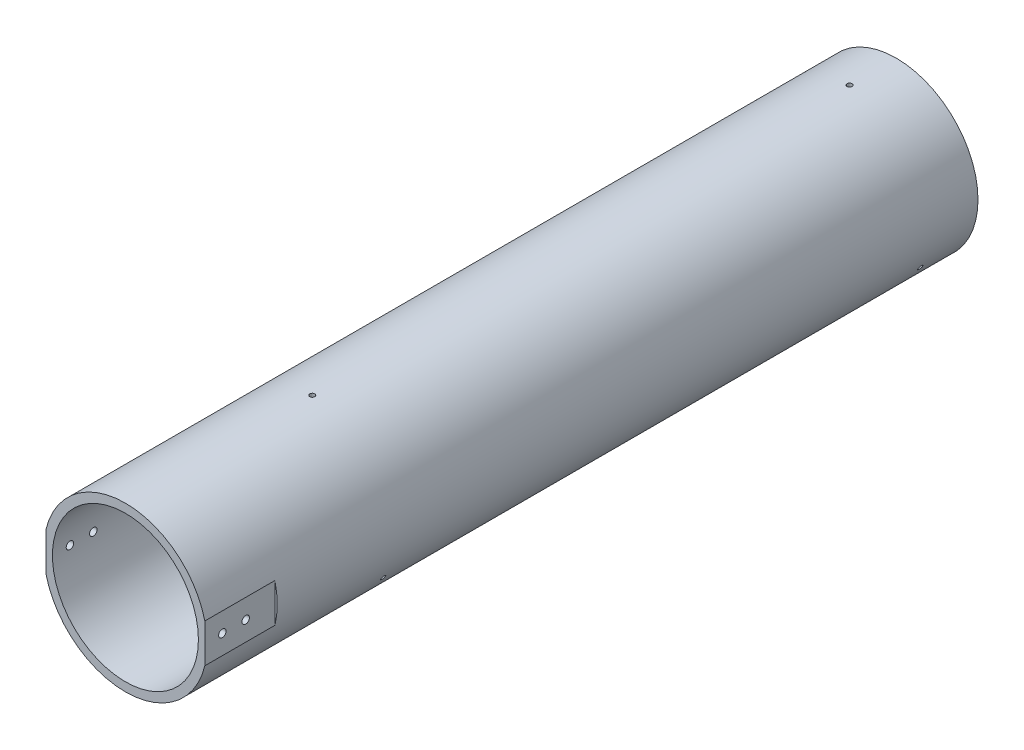
SolidWorks part; units mm, degrees
ref_plane "Front Plane" through (0, 0, 0) normal (0, 0, 1) x (1, 0, 0)
ref_plane "Top Plane" through (0, 0, 0) normal (0, 1, 0) x (1, 0, 0)
ref_plane "Right Plane" through (0, 0, 0) normal (1, 0, 0) x (0, 0, -1)
sketch "Sketch1" plane through (0, 0, 0) normal (0, 0, 1) x (1, 0, 0)
  circle A0 centre (0, 0) radius 39.6875
  circle A1 centre (0, 0) radius 44.45
  dimension "D1" = 88.9
  dimension "D2" = 79.375
extrude "Boss-Extrude1" add sketch "Sketch1" along normal mid plane 419.1
sketch "Sketch2" plane through (0, 0, 209.55) normal (0, 0, 1) x (1, 0, 0)
  line L1 (43.18, 13.8246) -> (51.0798, 13.8246)
  line L2 (43.18, 13.8246) -> (43.18, -14.6378)
  line L3 (43.18, -14.6378) -> (51.0798, -14.6378)
  line L4 (51.0798, 13.8246) -> (51.0798, -14.6378)
  dimension "D1" = 43.18
extrude "Cut-Extrude1" cut sketch "Sketch2" against normal blind 38.1
hole_wizard "#10-32 Tapped Hole1" positions "Sketch4" profile "Sketch3" tap size "#10-32" standard "ANSI Inch"
sketch "Sketch4" plane through (43.18, 0, 0) normal (1, 0, 0) x (0, 0, -1)
  line L0 (-209.55, 10.5494) -> (-209.55, -10.5494) construction
  point P0 (-200.025, 0)
  point P2 (-187.325, 0)
  dimension "D1" = 9.525
  dimension "D2" = 12.7
sketch "Sketch3" plane through (43.18, 0, 200.025) normal (0, 1, 0) x (0, 0, -1)
  line L0 (0, 0) -> (0, 14.9293)
  line L1 (0, 14.9293) -> (2.0193, 13.716)
  line L2 (2.0193, 13.716) -> (2.0193, 0)
  line L5 (2.0193, 0) -> (0, 0)
  line L10 (0, 14.9293) -> (-2.0193, 13.716) construction
  line L11 (0, -6.35) -> (0, 107.95) construction
  dimension "Tap Drill Dia." = 4.0386
  dimension "Tap Drill Depth" = 13.716
  dimension "Drill Angle" = 118
cosmetic thread "Hole Thread1" parameters "D1"=5.1335, "D2"=4.826
cosmetic thread "Hole Thread2" parameters "D1"=5.1335, "D2"=4.826
hole_wizard "#6-32 Tapped Hole1" positions "Sketch6" profile "Sketch5" tap size "#6-32" standard "ANSI Inch"
sketch "Sketch6" plane through (0, 0, -209.55) normal (0, 0, -1) x (-1, 0, 0)
  point P0 (0, 42.0688)
  point P2 (-42.0688, 0)
  point P4 (42.0688, 0)
  point P6 (0, -42.0688)
  dimension "D1" = 42.0688
  dimension "D2" = 42.0688
  dimension "D3" = 42.0688
  dimension "D4" = 42.0688
sketch "Sketch5" plane through (0, 42.0688, -209.55) normal (1, 0, 0) x (0, 1, 0)
  line L0 (0, 0) -> (0, 15.7987)
  line L1 (0, 15.7987) -> (1.3525, 14.986)
  line L2 (1.3525, 14.986) -> (1.3525, 0)
  line L5 (1.3525, 0) -> (0, 0)
  line L10 (0, 15.7987) -> (-1.3526, 14.986) construction
  line L11 (0, -6.35) -> (0, 107.95) construction
  dimension "Tap Drill Dia." = 2.7051
  dimension "Tap Drill Depth" = 14.986
  dimension "Drill Angle" = 118
cosmetic thread "Hole Thread3" parameters "D1"=10.922, "D2"=3.5052
cosmetic thread "Hole Thread4" parameters "D1"=10.922, "D2"=3.5052
cosmetic thread "Hole Thread5" parameters "D1"=10.922, "D2"=3.5052
cosmetic thread "Hole Thread6" parameters "D1"=10.922, "D2"=3.5052
mirror "Mirror1" about plane through (0, 0, 0) normal (1, 0, 0) of "#10-32 Tapped Hole1", "Cut-Extrude1"
hole_wizard "#6-32 Tapped Hole2" positions "3DSketch2" profile "Sketch8" tap size "#6-32" standard "ANSI Inch"
sketch3d "3DSketch2"
  point P0 (0, 44.45, -184.15)
  point P2 (0, 44.45, 107.95)
  dimension "D1" = 25.4
  dimension "D2" = 101.6
  dimension "D3" = 0
  dimension "D4" = 0
sketch "Sketch8" plane through (0, 44.45, -184.15) normal (1, 0, 0) x (0, 0, 1)
  line L0 (0, 0) -> (0, 88.9)
  line L1 (0, 88.9) -> (1.3525, 88.9)
  line L2 (1.3525, 88.9) -> (1.3525, 0)
  line L5 (1.3525, 0) -> (0, 0)
  line L11 (0, -6.35) -> (0, 107.95) construction
  dimension "Thru Tap Drill Dia." = 2.7051
  dimension "Thru Tap Drill Depth" = 88.9
cosmetic thread "Hole Thread7" parameters "D2"=3.5052
cosmetic thread "Hole Thread8" parameters "D2"=3.5052
pattern_circular "CirPattern1" count 3 over 360 about axis through (0, 0, -209.55) along (0, 0, 1) of "#6-32 Tapped Hole2"
